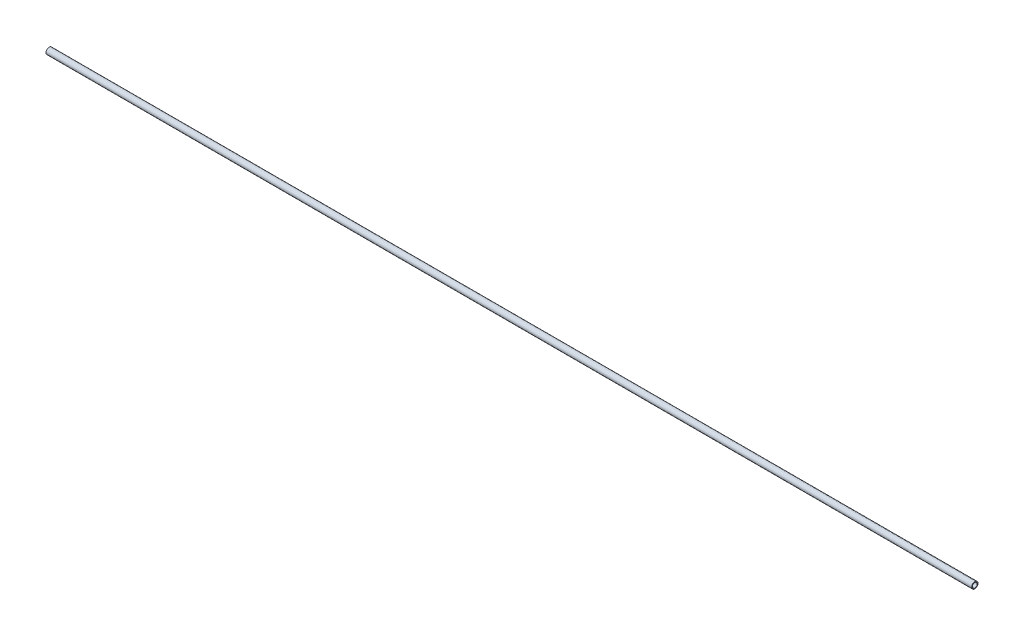
SolidWorks part; units mm, degrees
material "AISI 4130 Steel, annealed at 865C"
ref_plane "Front Plane" through (0, 0, 0) normal (0, 0, 1) x (1, 0, 0)
ref_plane "Top Plane" through (0, 0, 0) normal (0, 1, 0) x (1, 0, 0)
ref_plane "Right Plane" through (0, 0, 0) normal (1, 0, 0) x (0, 0, -1)
sketch "Sketch1" plane through (0, 0, 0) normal (1, 0, 0) x (0, 0, -1)
  circle A0 centre (0, 0) radius 12.7
  circle A1 centre (0, 0) radius 9.652
  dimension "D1" = 25.4
  dimension "D2" = 19.304
extrude "Boss-Extrude1" add sketch "Sketch1" along normal blind 3733.8
